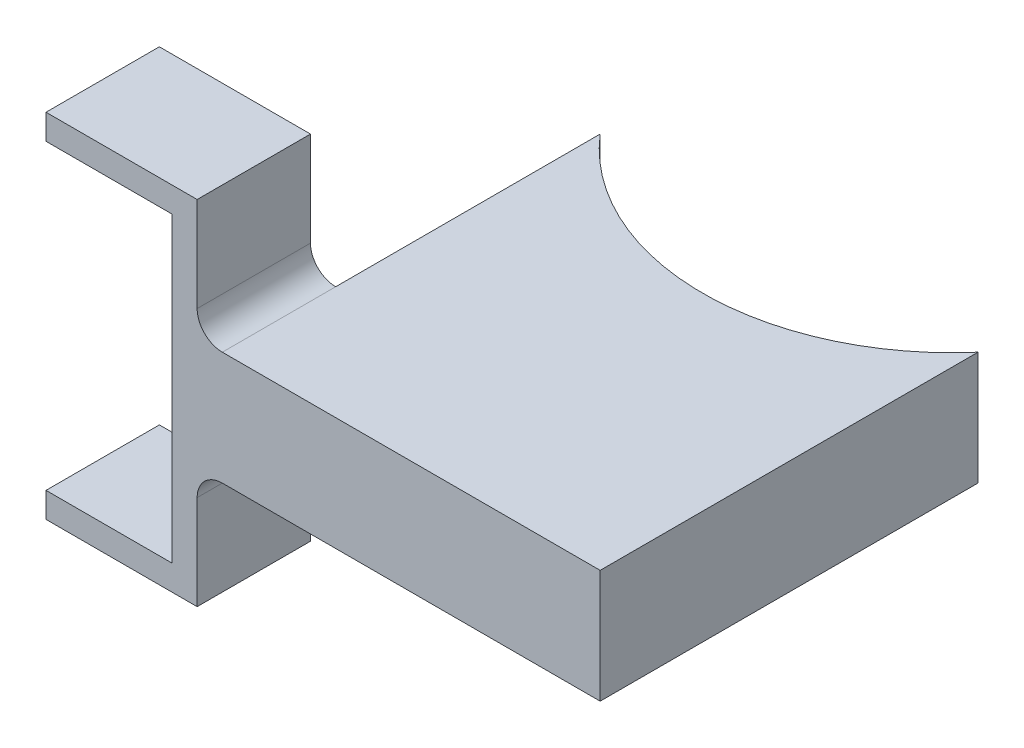
SolidWorks part; units mm, degrees
ref_plane "前视基准面" through (0, 0, 0) normal (0, 0, 1) x (1, 0, 0)
ref_plane "上视基准面" through (0, 0, 0) normal (0, 1, 0) x (1, 0, 0)
ref_plane "右视基准面" through (0, 0, 0) normal (1, 0, 0) x (0, 0, -1)
sketch "草图1" plane through (0, 0, 0) normal (0, 1, 0) x (1, 0, 0)
  line L1 (-14.1459, 29.5401) -> (15.8541, 29.5401)
  line L2 (-14.1459, 29.5401) -> (-14.1459, -0.4599)
  line L3 (-14.1459, -0.4599) -> (15.8541, -0.4599)
  line L4 (15.8541, 29.5401) -> (15.8541, -0.4599)
  circle A0 centre (0.8541, 42.4645) radius 19.8
  dimension "D3" = 39.6
  dimension "D1" = 30
  dimension "D2" = 30
extrude "凸台-拉伸1" add sketch "草图1" along normal blind 9 contours A0 L2 L3 L4
sketch "草图2" plane through (-14.1459, 0, 0) normal (-1, 0, 0) x (0, 0, 1)
  line L0 (-29.5401, 9) -> (0.4599, 9) construction
  line L1 (0.4599, 0) -> (-8.5401, 0)
  line L2 (0.4599, 0) -> (0.4599, 9)
  line L3 (0.4599, 9) -> (-8.5401, 9)
  line L4 (-8.5401, 0) -> (-8.5401, 9)
extrude "凸台-拉伸2" add sketch "草图2" along normal blind 2
sketch "草图3" plane through (0, 9, 0) normal (0, 1, 0) x (1, 0, 0)
  line L6 (-16.1459, 8.5401) -> (-18.1459, 8.5401)
  line L7 (-16.1459, 8.5401) -> (-16.1459, -0.4599)
  line L8 (-16.1459, -0.4599) -> (-18.1459, -0.4599)
  line L9 (-18.1459, 8.5401) -> (-18.1459, -0.4599)
  dimension "D1" = 9
  dimension "D2" = 2
extrude "凸台-拉伸5" add sketch "草图3" along normal blind 9.5 and the other way blind 18.5
sketch "草图5" plane through (-18.1459, 0, 0) normal (-1, 0, 0) x (0, 0, 1)
  line L0 (0.4599, -9.5) -> (0.4599, 18.5) construction
  line L1 (-8.5401, 18.5) -> (0.4599, 18.5)
  line L2 (-8.5401, 18.5) -> (-8.5401, 16.5)
  line L3 (-8.5401, 16.5) -> (0.4599, 16.5)
  line L4 (0.4599, 18.5) -> (0.4599, 16.5)
  line L6 (-8.5401, -9.5) -> (0.4599, -9.5)
  line L7 (-8.5401, -9.5) -> (-8.5401, -7.5)
  line L8 (-8.5401, -7.5) -> (0.4599, -7.5)
  line L9 (0.4599, -9.5) -> (0.4599, -7.5)
  dimension "D1" = 2
  dimension "D2" = 2
extrude "凸台-拉伸6" add sketch "草图5" along normal blind 10
fillet "圆角2" radius 2 2 edges at (-16.1459, 0, -4.0401) (-16.1459, 9, -4.0401)
